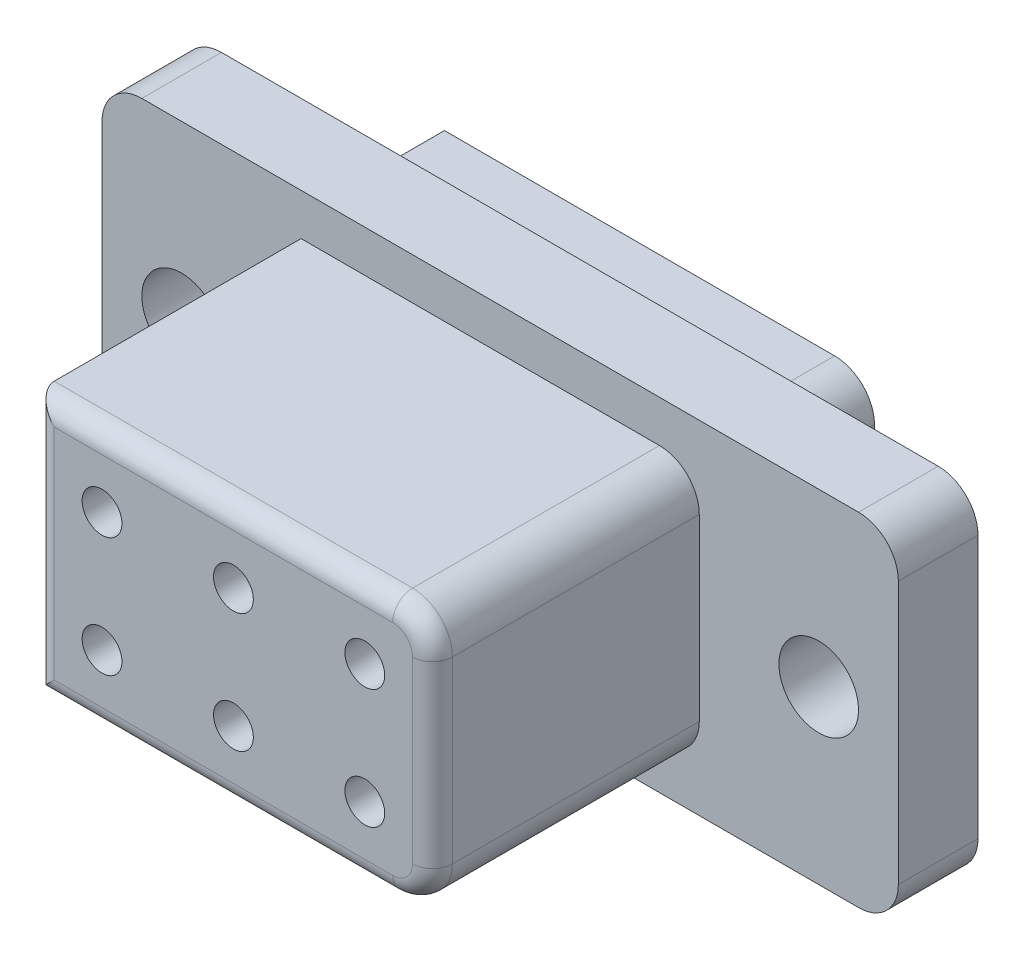
SolidWorks part; units mm, degrees
ref_plane "前视基准面" through (0, 0, 0) normal (0, 0, 1) x (1, 0, 0)
ref_plane "上视基准面" through (0, 0, 0) normal (0, 1, 0) x (1, 0, 0)
ref_plane "右视基准面" through (0, 0, 0) normal (1, 0, 0) x (0, 0, -1)
other "Configuration Table"
sketch "草图2" plane through (0, 0, 0) normal (0, 0, 1) x (1, 0, 0)
  line L0 (-3.3, 1.5) -> (0, 1.5) construction
  line L1 (-5, 3.25) -> (5, 3.25)
  line L2 (-5, 3.25) -> (-5, -3.25)
  line L3 (-5, -3.25) -> (5, -3.25)
  line L4 (5, 3.25) -> (5, -3.25)
  line L5 (-5, 3.25) -> (5, -3.25) construction
  line L6 (-5, -3.25) -> (5, 3.25) construction
  line L7 (-3.3, 1.5) -> (-3.3, -1.5) construction
  circle A0 centre (-3.3, 1.5) radius 0.5
  circle A1 centre (0, 1.5) radius 0.5
  circle A2 centre (3.3, 1.5) radius 0.5
  circle A3 centre (0, -1.5) radius 0.5
  circle A4 centre (3.3, -1.5) radius 0.5
  circle A5 centre (-3.3, -1.5) radius 0.5
  point P0 (0, 0)
  dimension "D8" = 1
  dimension "D1" = 6.5
  dimension "D2" = 10
  dimension "D3" = 1.7
  dimension "D4" = 1.75
  dimension "D5" = 3.3
  dimension "D9" = 3
  dimension "D10" = 90
  dimension "D6" = 3
  dimension "D7" = 2
extrude "凸台-拉伸1" add sketch "草图2" along normal blind 6.7
sketch "草图4" plane through (0, 0, 0) normal (0, 0, 1) x (1, 0, 0)
  line L0 (0, 0) -> (0, 6.7822) construction
  line L1 (-10, 4.3) -> (10, 4.3)
  line L2 (-10, 4.3) -> (-10, -4.3)
  line L3 (-10, -4.3) -> (10, -4.3)
  line L4 (10, 4.3) -> (10, -4.3)
  line L5 (-10, 4.3) -> (10, -4.3) construction
  line L6 (-10, -4.3) -> (10, 4.3) construction
  circle A0 centre (-8, 0) radius 1
  circle A1 centre (8, 0) radius 1
  point P0 (0, 0)
  dimension "D3" = 2
  dimension "D1" = 8.6
  dimension "D2" = 20
  dimension "D4" = 16
  dimension "D5" = 4.3
extrude "凸台-拉伸2" add sketch "草图4" against normal blind 2
sketch "草图7" plane through (0, 0, -2) normal (0, 0, -1) x (-1, 0, 0)
  line L0 (-3.3, 1.5) -> (0, 1.5) construction
  line L1 (-5.4, 3.4) -> (5.4, 3.4)
  line L2 (-5.4, 3.4) -> (-5.4, -3.4)
  line L3 (-5.4, -3.4) -> (5.4, -3.4)
  line L4 (5.4, 3.4) -> (5.4, -3.4)
  line L5 (-5.4, 3.4) -> (5.4, -3.4) construction
  line L6 (-5.4, -3.4) -> (5.4, 3.4) construction
  line L7 (-3.3, 1.5) -> (-3.3, -1.5) construction
  circle A0 centre (-3.3, 1.5) radius 0.5
  circle A1 centre (0, 1.5) radius 0.5
  circle A2 centre (3.3, 1.5) radius 0.5
  circle A3 centre (0, -1.5) radius 0.5
  circle A4 centre (3.3, -1.5) radius 0.5
  circle A5 centre (-3.3, -1.5) radius 0.5
  point P0 (0, 0)
  dimension "D10" = 1
  dimension "D1" = 10.8
  dimension "D2" = 6.8
  dimension "D3" = 90
  dimension "D4" = 3.3
  dimension "D5" = 3
  dimension "D6" = 1.9
  dimension "D7" = 2.1
  dimension "D8" = 3
  dimension "D9" = 2
extrude "凸台-拉伸3" add sketch "草图7" along normal blind 2
fillet "圆角1" radius 1 4 edges at (-10, -4.3, -1) (-10, 4.3, -1) (10, -4.3, -1) (10, 4.3, -1)
fillet "圆角2" radius 1 4 edges at (5, -3.25, 3.35) (5, 3.25, 3.35) (5.4, 3.4, -3) (5.4, -3.4, -3)
fillet "圆角4" radius 0.5 6 edges at (4.7071, 2.9571, 6.7) (4.7071, -2.9571, 6.7) (5, 0, 6.7) (-0.5, 3.25, 6.7) (-5, 0, 6.7) (-0.5, -3.25, 6.7)
